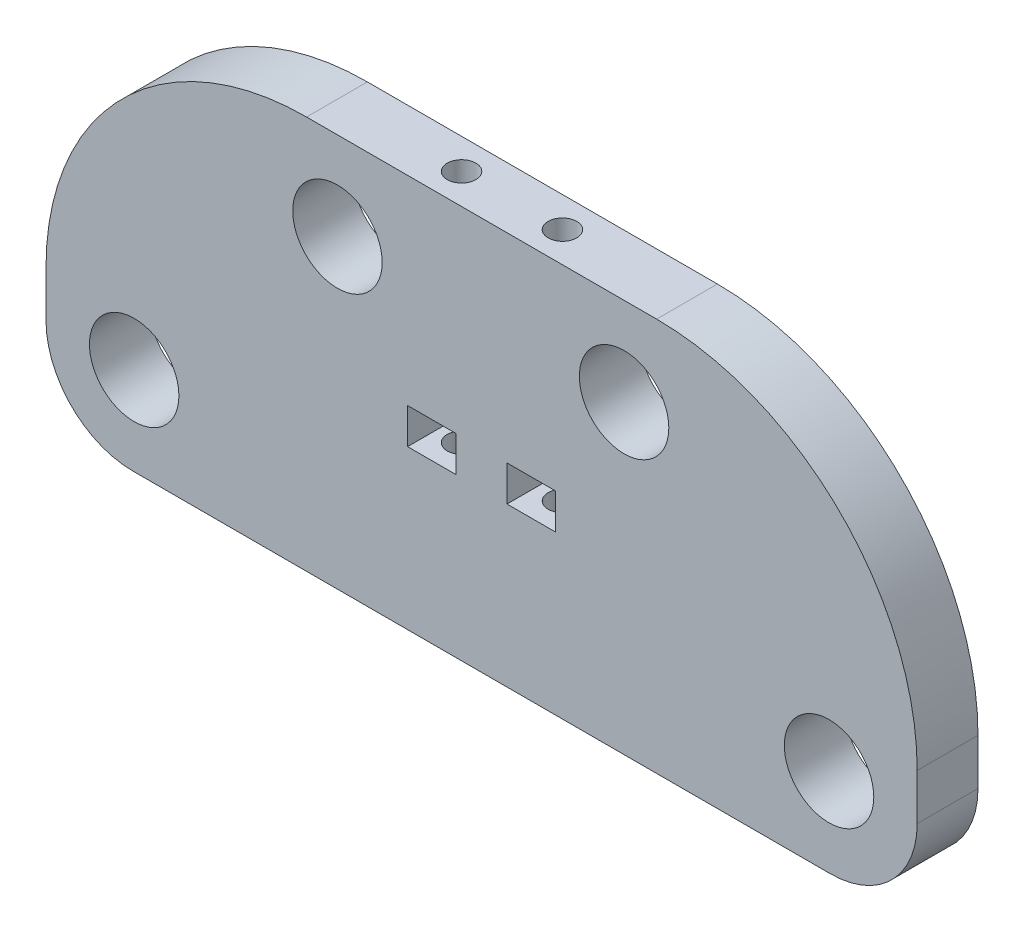
SolidWorks part; units mm, degrees
ref_plane "Plano frontal" through (0, 0, 0) normal (0, 0, 1) x (1, 0, 0)
ref_plane "Plano superior" through (0, 0, 0) normal (0, 1, 0) x (1, 0, 0)
ref_plane "Plano direito" through (0, 0, 0) normal (1, 0, 0) x (0, 0, -1)
sketch "Esboço1" plane through (0, 0, 0) normal (0, 0, 1) x (1, 0, 0)
  line L0 (-39.9126, -26.5911) -> (40.0874, -26.5911) construction
  line L5 (-24.4818, 13.7089) -> (50.2374, -28.131) construction
  line L6 (-50.0626, -27.9516) -> (24.5532, 13.7089) construction
  line L7 (-11.3586, 3.5589) -> (11.3414, 3.5589) construction
  line L9 (-39.9126, -26.5911) -> (-39.9126, -31.5911) construction
  line L10 (-11.3586, 3.5589) -> (-11.3586, 8.4072) construction
  line L16 (0.0874, 13.7089) -> (0.0874, -31.5911) construction
  line L17 (-50.0626, -31.5911) -> (50.2374, -31.5911)
  line L22 (-45.0626, -21.4411) -> (-50.0626, -21.4411) construction
  line L23 (0.0874, 5.2627) -> (-11.3586, 5.2627) construction
  line L32 (-50.0626, 13.7089) -> (-50.0626, -31.5911)
  line L35 (45.2374, -21.4411) -> (50.2374, -21.4411) construction
  line L44 (50.2374, 13.7089) -> (50.2374, -31.5911)
  line L54 (-2.8356, -13.3411) -> (-8.4356, -13.3411)
  line L61 (-50.0626, -16.68) -> (50.2374, -16.68) construction
  line L69 (3.0104, -9.2411) -> (8.6104, -9.2411)
  line L70 (5.8104, 13.7089) -> (5.8104, -11.2911) construction
  line L74 (3.0104, -9.2411) -> (3.0104, -13.3411)
  line L80 (16.4914, 8.7089) -> (16.4914, 13.7089) construction
  line L81 (50.2374, 13.7089) -> (-50.0626, 13.7089)
  line L82 (-16.5086, -1.5911) -> (16.4914, -1.5911) construction
  line L83 (3.0104, -13.3411) -> (8.6104, -13.3411)
  line L84 (8.6104, -9.2411) -> (8.6104, -13.3411)
  line L85 (3.0104, -9.2411) -> (8.6104, -13.3411) construction
  line L86 (3.0104, -13.3411) -> (8.6104, -9.2411) construction
  line L87 (-8.4356, -9.2411) -> (-8.4356, -13.3411)
  line L88 (-2.8356, -9.2411) -> (-8.4356, -9.2411)
  line L89 (-2.8356, -9.2411) -> (-2.8356, -13.3411)
  circle A7 centre (-16.5086, 3.5589) radius 5.15
  circle A8 centre (16.4914, 3.5589) radius 5.15
  circle A17 centre (-39.9126, -21.4411) radius 5.15
  circle A18 centre (40.0874, -21.4411) radius 5.15
  point P0 (0, 0)
  dimension "D6" = 10.3
  dimension "D9" = 5
  dimension "D8" = 5.6
  dimension "D7" = 10.3
  dimension "D1" = 5
  dimension "D2" = 5
  dimension "D3" = 5
  dimension "D4" = 25
  dimension "D5" = 22.7
  dimension "D10" = 4.1
extrude "Ressalto-extrusão1" add sketch "Esboço1" along normal blind 7
sketch "Esboço2" plane through (0, 13.7089, 0) normal (0, 1, 0) x (1, 0, 0)
  line L0 (0.0874, 0) -> (0.0874, -7) construction
  line L1 (50.2374, 0) -> (-50.0626, 0) construction
  line L2 (50.2374, -7) -> (-50.0626, -7) construction
  line L3 (0.0874, -3.5) -> (-5.7226, -3.5) construction
  circle A0 centre (-5.7226, -3.5) radius 1.65
  circle A1 centre (5.8974, -3.5) radius 1.65
  dimension "D2" = 3.3
  dimension "D1" = 5.81
extrude "Corte-extrusão1" cut sketch "Esboço2" against normal blind 35
fillet "Filete1" radius 10 2 edges at (50.2374, -31.5911, 3.5) (-50.0626, -31.5911, 3.5)
fillet "Filete2" radius 30 2 edges at (-50.0626, 13.7089, 3.5) (50.2374, 13.7089, 3.5)
